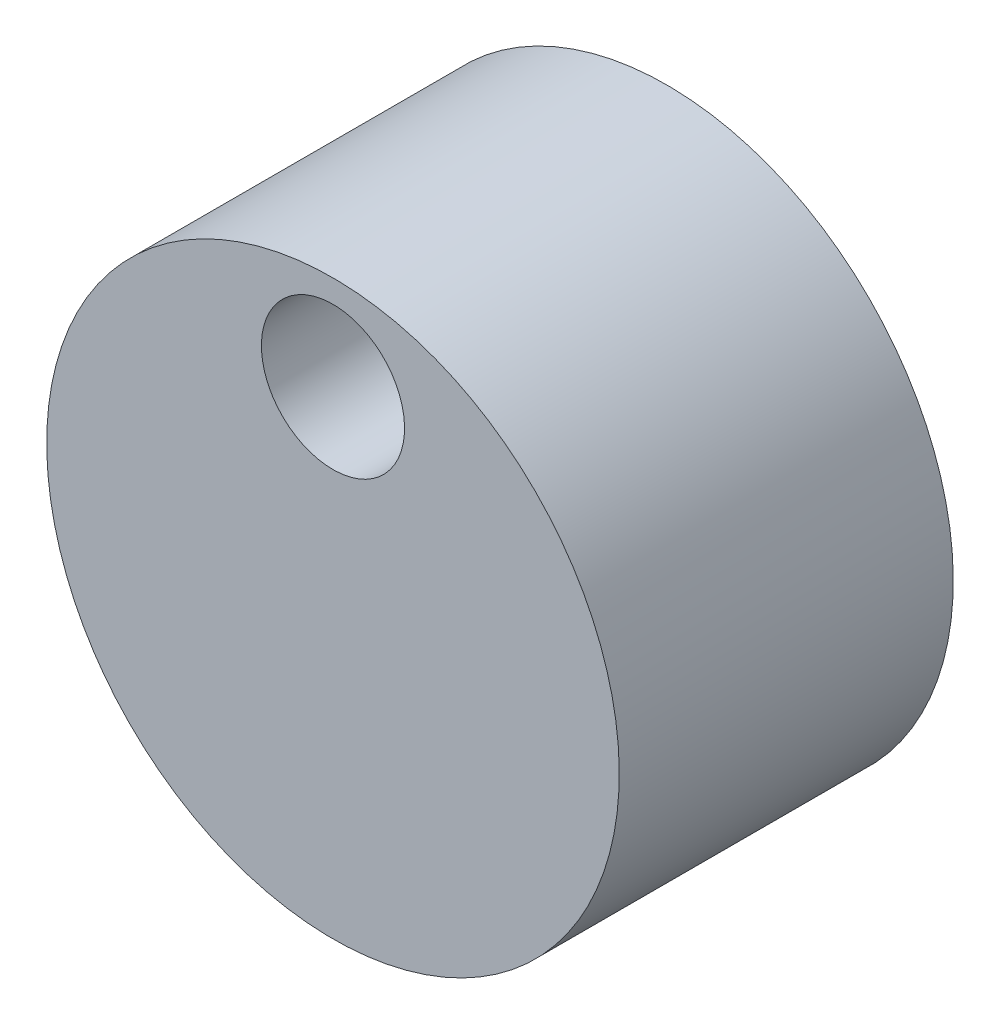
SolidWorks part; units mm, degrees
ref_plane "Plan de face" through (0, 0, 0) normal (0, 0, 1) x (1, 0, 0)
ref_plane "Plan de dessus" through (0, 0, 0) normal (0, 1, 0) x (1, 0, 0)
ref_plane "Plan de droite" through (0, 0, 0) normal (1, 0, 0) x (0, 0, -1)
sketch "Esquisse2" plane through (0, 0, 0) normal (0, 0, 1) x (1, 0, 0)
  line L0 (0, 0) -> (0, 8.509) construction
  ellipse E0 centre (0, 0) end of major axis (-9.6375, -8.271) minor radius 12.7
  ellipse E1 centre (0, 8.509) end of major axis (2.6707, 10.226) minor radius 3.175
extrude "Boss.-Extru.2" add sketch "Esquisse2" along normal blind 14.8158
sketch "Esquisse3" plane through (0, 0, 0) normal (0, 0, -1) x (-1, 0, 0)
  line L0 (0, 0) -> (0, 8.509) construction
